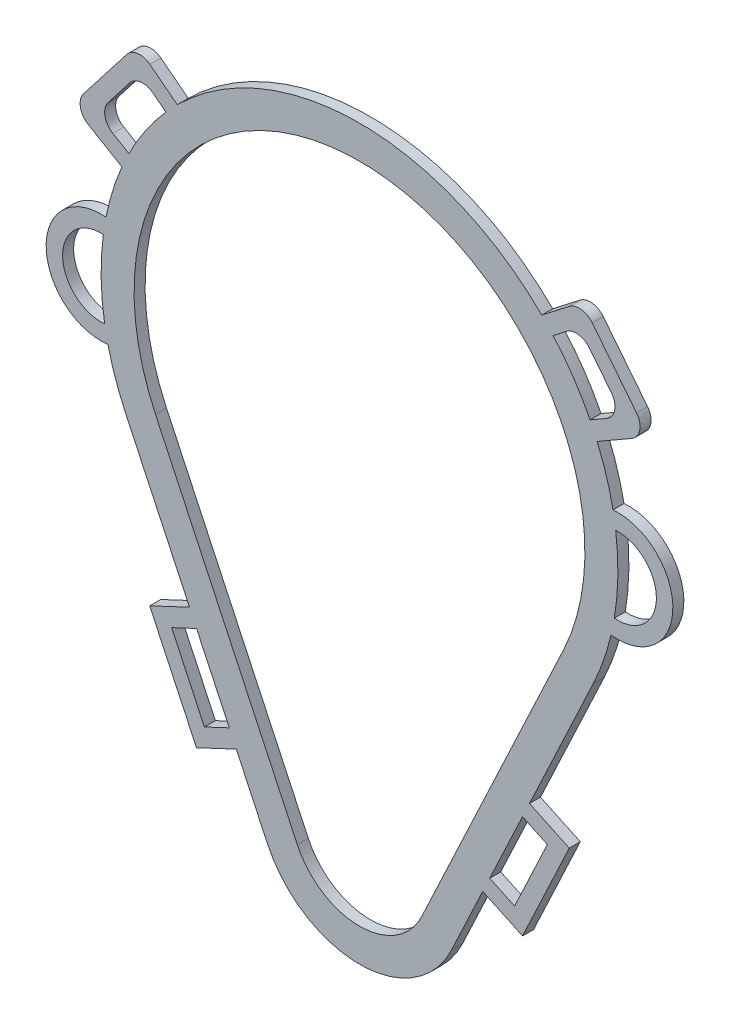
SolidWorks part; units mm, degrees
ref_plane "Front Plane" through (0, 0, 0) normal (0, 0, 1) x (1, 0, 0)
ref_plane "Top Plane" through (0, 0, 0) normal (0, 1, 0) x (1, 0, 0)
ref_plane "Right Plane" through (0, 0, 0) normal (1, 0, 0) x (0, 0, -1)
sketch "Sketch1" plane through (0, 0, 0) normal (0, 0, 1) x (1, 0, 0)
  line L0 (0, 41) -> (0, -67) construction
  line L1 (37.1057, -17.4403) -> (11.3127, -72.3172)
  line L2 (-37.1057, -17.4403) -> (-11.3127, -72.3172)
  line L3 (-42.5358, -19.9925) -> (-16.7428, -74.8694)
  line L4 (42.5358, -19.9925) -> (16.7428, -74.8694)
  arc A0 (37.1057, -17.4403) -> (-37.1057, -17.4403) centre (0, 0) ccw
  arc A1 (-11.3127, -72.3172) -> (11.3127, -72.3172) centre (0, -67) ccw
  arc A2 (42.5358, -19.9925) -> (-42.5358, -19.9925) centre (0, 0) ccw
  arc A3 (-16.7428, -74.8694) -> (16.7428, -74.8694) centre (0, -67) ccw
  dimension "D1" = 6
  dimension "D2" = 41
  dimension "D3" = 12.5
extrude "Boss-Extrude1" add sketch "Sketch1" along normal blind 2
sketch "Sketch2" plane through (0, 0, 2) normal (0, 0, 1) x (1, 0, 0)
  line L0 (29.6393, -47.431) -> (34.1644, -49.5578)
  line L1 (16.7428, -74.8694) -> (42.5358, -19.9925) construction
  line L2 (34.1644, -49.5578) -> (28.2092, -62.2281)
  line L3 (28.2092, -62.2281) -> (23.6841, -60.1012)
  line L4 (0, 49.5385) -> (0, -93.5909) construction
  line L5 (29.6393, -47.431) -> (23.6841, -60.1012)
  line L6 (38.1556, -48.1189) -> (29.6481, -66.2193)
  line L7 (29.6481, -66.2193) -> (19.6929, -61.5402)
  line L8 (28.2004, -43.4398) -> (19.6929, -61.5402)
  line L9 (28.2004, -43.4398) -> (38.1556, -48.1189)
  line L10 (-28.2004, -43.4398) -> (-38.1556, -48.1189)
  line L11 (-28.2004, -43.4398) -> (-19.6929, -61.5402)
  line L12 (-29.6481, -66.2193) -> (-19.6929, -61.5402)
  line L13 (-38.1556, -48.1189) -> (-29.6481, -66.2193)
  line L14 (-29.6393, -47.431) -> (-23.6841, -60.1012)
  line L15 (-28.2092, -62.2281) -> (-23.6841, -60.1012)
  line L16 (-34.1644, -49.5578) -> (-28.2092, -62.2281)
  line L17 (-29.6393, -47.431) -> (-34.1644, -49.5578)
  dimension "D1" = 14
  dimension "D2" = 5
  dimension "D3" = 3
extrude "Boss-Extrude2" add sketch "Sketch2" against normal blind 2
sketch "Sketch3" plane through (0, 0, 2) normal (0, 0, 1) x (1, 0, 0)
  line L0 (-35.214, 31.1284) -> (-37.5839, 32.9678)
  line L1 (-41.9377, 21.2186) -> (-44.876, 22.9491)
  line L2 (-41.7933, 32.4372) -> (-45.7234, 27.3735)
  line L3 (-35.214, 31.1284) -> (-41.9377, 21.2186)
  line L4 (-31.1514, 31.7728) -> (-38.1145, 37.1771)
  line L5 (-42.3238, 36.6466) -> (-50.1841, 26.519)
  line L6 (-41.0353, 17.2054) -> (-49.3367, 22.0947)
  line L7 (-31.1514, 31.7728) -> (-41.0353, 17.2054)
  line L8 (0, 0) -> (0, 76.5871) construction
  line L9 (31.1514, 31.7728) -> (41.0353, 17.2054)
  line L10 (41.0353, 17.2054) -> (49.5212, 22.0823)
  line L11 (42.3292, 36.6913) -> (50.3766, 26.5479)
  line L12 (31.1514, 31.7728) -> (38.1396, 37.1966)
  line L13 (35.214, 31.1284) -> (41.9377, 21.2186)
  line L14 (41.7986, 32.4819) -> (45.8142, 27.4204)
  line L15 (41.9377, 21.2186) -> (44.9589, 22.9548)
  line L16 (35.214, 31.1284) -> (37.6091, 32.9873)
  line L17 (-35.214, 31.1284) -> (-39.9539, 34.8072) construction
  line L18 (-39.9539, 34.8072) -> (-47.8142, 24.6797) construction
  line L19 (-31.1514, 31.7728) -> (-40.4844, 39.0165) construction
  line L20 (-40.4844, 39.0165) -> (-52.2749, 23.8252) construction
  line L21 (-41.0353, 17.2054) -> (-52.2749, 23.8252) construction
  line L22 (-41.9377, 21.2186) -> (-47.8142, 24.6797) construction
  circle A1 centre (-38.8928, 26.3885) radius 6 construction
  arc A2 (42.5358, -19.9925) -> (-42.5358, -19.9925) centre (0, 0) ccw construction
  circle A3 centre (38.8928, 26.3885) radius 6 construction
  arc A4 (-37.5839, 32.9678) -> (-41.7933, 32.4372) centre (-39.4233, 30.5978) ccw
  arc A5 (-38.1145, 37.1771) -> (-42.3238, 36.6466) centre (-39.9539, 34.8072) ccw
  arc A6 (-49.3367, 22.0947) -> (-50.1841, 26.519) centre (-47.8142, 24.6797) cw
  arc A7 (-44.876, 22.9491) -> (-45.7234, 27.3735) centre (-43.3535, 25.5341) cw
  arc A8 (44.9589, 22.9548) -> (45.8142, 27.4204) centre (43.464, 25.5559) ccw
  arc A9 (49.5212, 22.0823) -> (50.3766, 26.5479) centre (48.0264, 24.6833) ccw
  arc A10 (42.3292, 36.6913) -> (38.1396, 37.1966) centre (39.979, 34.8267) ccw
  arc A11 (37.6091, 32.9873) -> (41.7986, 32.4819) centre (39.4484, 30.6173) cw
  point P29 (-39.9539, 34.8072)
  point P33 (-40.4844, 39.0165)
  point P46 (40.4844, 39.0165)
  point P49 (39.9539, 34.8072)
  dimension "D1" = 3
  dimension "D2" = 12
  dimension "D3" = 3
  dimension "D4" = 3
extrude "Boss-Extrude3" add sketch "Sketch3" against normal blind 2
sketch "Sketch4" plane through (0, 0, 2) normal (0, 0, 1) x (1, 0, 0)
  line L0 (45.8484, 6.0673) -> (45.8484, -7.7445)
  line L1 (42.8484, 8.2623) -> (42.8484, -9.9395)
  line L2 (0, 0) -> (0, 26.9586) construction
  line L3 (-42.8484, 8.2623) -> (-42.8484, -9.9395)
  line L4 (-45.8484, 6.0673) -> (-45.8484, -7.7445)
  arc A0 (42.5358, -19.9925) -> (43.2221, 18.4621) centre (0, 0) ccw construction
  arc A1 (45.8484, -7.7445) -> (45.8484, 6.0673) centre (46.9925, -0.8386) ccw
  arc A2 (42.8484, -9.9395) -> (42.8484, 8.2623) centre (46.9925, -0.8386) ccw
  arc A3 (-42.8484, -9.9395) -> (-42.8484, 8.2623) centre (-46.9925, -0.8386) cw
  arc A4 (-45.8484, -7.7445) -> (-45.8484, 6.0673) centre (-46.9925, -0.8386) cw
  dimension "D1" = 3
extrude "Boss-Extrude4" add sketch "Sketch4" against normal blind 2
